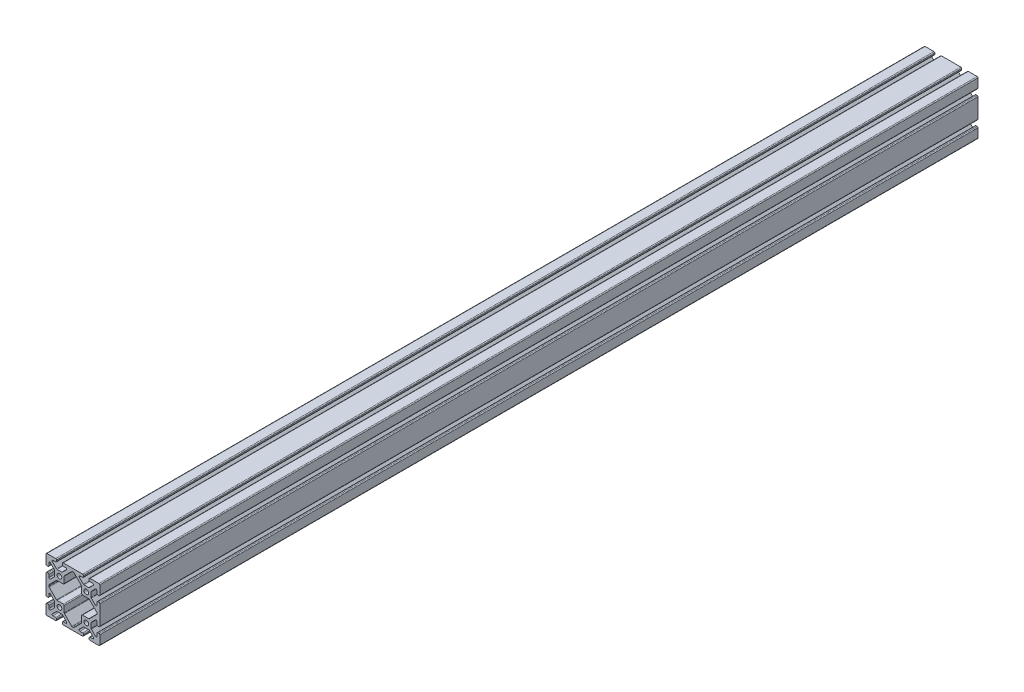
SolidWorks part; units mm, degrees
material "6061 Alloy"
ref_plane "Front Plane" through (0, 0, 0) normal (0, 0, 1) x (1, 0, 0)
ref_plane "Top Plane" through (0, 0, 0) normal (0, 1, 0) x (1, 0, 0)
ref_plane "Right Plane" through (0, 0, 0) normal (1, 0, 0) x (0, 0, -1)
sketch "Sketch1" plane through (0, 0, 0) normal (0, 0, 1) x (1, 0, 0)
  line L0 (-6.7564, 3.8827) -> (-6.7564, -6.7564)
  line L1 (-57.15, 19.05) -> (19.05, 19.05) construction
  line L2 (-6.7564, -6.7564) -> (3.8827, -6.7564)
  line L3 (-20.2403, -53.086) -> (-17.8597, -53.086)
  line L4 (19.05, 19.05) -> (19.05, -19.05) construction
  line L5 (-6.7564, -41.9827) -> (-17.8597, -53.086)
  line L6 (-20.2403, 14.986) -> (-17.8597, 14.986)
  line L7 (0, 0) -> (50000, 0) construction
  line L8 (-12.1123, 14.986) -> (-3.8827, 6.7564)
  line L9 (-34.036, 19.05) -> (-4.064, 19.05)
  line L10 (-4.064, 19.05) -> (-4.064, 14.986)
  line L11 (-4.064, 14.986) -> (-12.1123, 14.986)
  line L12 (-3.8827, 6.7564) -> (3.8827, 6.7564)
  line L13 (-6.7564, 3.8827) -> (-17.8597, 14.986)
  line L14 (-19.05, 19.05) -> (-19.05, 50019.05) construction
  line L15 (-57.15, 19.05) -> (-57.15, -19.05) construction
  line L16 (-53.086, -17.8597) -> (-53.086, -20.2403)
  line L17 (3.8827, -31.3436) -> (-6.7564, -31.3436)
  line L18 (19.05, 4.064) -> (14.986, 4.064)
  line L19 (19.05, 19.05) -> (19.05, 4.064)
  line L20 (14.986, 4.064) -> (14.986, 12.1123)
  line L21 (14.986, 12.1123) -> (6.7564, 3.8827)
  line L22 (6.7564, 3.8827) -> (6.7564, -3.8827)
  line L23 (12.1123, 14.986) -> (3.8827, 6.7564)
  line L24 (4.064, 14.986) -> (12.1123, 14.986)
  line L25 (4.064, 19.05) -> (4.064, 14.986)
  line L26 (19.05, 19.05) -> (4.064, 19.05)
  line L27 (14.986, -12.1123) -> (6.7564, -3.8827)
  line L28 (14.986, -4.064) -> (14.986, -12.1123)
  line L29 (19.05, -4.064) -> (14.986, -4.064)
  line L30 (19.05, -34.036) -> (19.05, -4.064)
  line L31 (-6.7564, -31.3436) -> (-6.7564, -41.9827)
  line L32 (-25.9877, -53.086) -> (-34.2173, -44.8564)
  line L33 (-34.036, -57.15) -> (-34.036, -53.086)
  line L34 (3.8827, -6.7564) -> (14.986, -17.8597)
  line L35 (-34.036, -53.086) -> (-25.9877, -53.086)
  line L36 (-34.2173, -44.8564) -> (-41.9827, -44.8564)
  line L37 (-57.15, -42.164) -> (-53.086, -42.164)
  line L38 (3.8827, -31.3436) -> (14.986, -20.2403)
  line L39 (-57.15, -57.15) -> (-57.15, -42.164)
  line L40 (-53.086, -42.164) -> (-53.086, -50.2123)
  line L41 (-53.086, -50.2123) -> (-44.8564, -41.9827)
  line L42 (-44.8564, -41.9827) -> (-44.8564, -34.2173)
  line L43 (-50.2123, -53.086) -> (-41.9827, -44.8564)
  line L44 (19.05, -34.036) -> (14.986, -34.036)
  line L45 (14.986, -34.036) -> (14.986, -25.9877)
  line L46 (14.986, -25.9877) -> (6.7564, -34.2173)
  line L47 (19.05, -57.15) -> (4.064, -57.15)
  line L48 (4.064, -57.15) -> (4.064, -53.086)
  line L49 (4.064, -53.086) -> (12.1123, -53.086)
  line L50 (12.1123, -53.086) -> (3.8827, -44.8564)
  line L51 (6.7564, -41.9827) -> (6.7564, -34.2173)
  line L52 (14.986, -50.2123) -> (6.7564, -41.9827)
  line L53 (14.986, -42.164) -> (14.986, -50.2123)
  line L54 (19.05, -57.15) -> (19.05, -42.164)
  line L55 (19.05, -42.164) -> (14.986, -42.164)
  line L56 (-42.164, -53.086) -> (-50.2123, -53.086)
  line L57 (-42.164, -57.15) -> (-42.164, -53.086)
  line L58 (-57.15, -57.15) -> (-42.164, -57.15)
  line L59 (-53.086, -25.9877) -> (-44.8564, -34.2173)
  line L60 (-53.086, -34.036) -> (-53.086, -25.9877)
  line L61 (-3.8827, -44.8564) -> (3.8827, -44.8564)
  line L62 (-4.064, -53.086) -> (-12.1123, -53.086)
  line L63 (-4.064, -57.15) -> (-4.064, -53.086)
  line L64 (-34.036, -57.15) -> (-4.064, -57.15)
  line L65 (-12.1123, -53.086) -> (-3.8827, -44.8564)
  line L66 (-57.15, -34.036) -> (-53.086, -34.036)
  line L67 (14.986, -17.8597) -> (14.986, -20.2403)
  line L68 (-41.9827, -31.3436) -> (-53.086, -20.2403)
  line L69 (-41.9827, -6.7564) -> (-53.086, -17.8597)
  line L70 (-31.3436, -31.3436) -> (-31.3436, -41.9827)
  line L71 (-57.15, -34.036) -> (-57.15, -4.064)
  line L72 (-57.15, -4.064) -> (-53.086, -4.064)
  line L73 (-53.086, -4.064) -> (-53.086, -12.1123)
  line L74 (-53.086, -12.1123) -> (-44.8564, -3.8827)
  line L75 (-57.15, 19.05) -> (-42.164, 19.05)
  line L76 (-42.164, 19.05) -> (-42.164, 14.986)
  line L77 (-42.164, 14.986) -> (-50.2123, 14.986)
  line L78 (-50.2123, 14.986) -> (-41.9827, 6.7564)
  line L79 (-44.8564, 3.8827) -> (-44.8564, -3.8827)
  line L80 (-53.086, 12.1123) -> (-44.8564, 3.8827)
  line L81 (-53.086, 4.064) -> (-53.086, 12.1123)
  line L82 (-57.15, 19.05) -> (-57.15, 4.064)
  line L83 (-57.15, 4.064) -> (-53.086, 4.064)
  line L84 (-41.9827, -31.3436) -> (-31.3436, -31.3436)
  line L85 (-31.3436, 3.8827) -> (-20.2403, 14.986)
  line L86 (-34.2173, 6.7564) -> (-41.9827, 6.7564)
  line L87 (-34.036, 14.986) -> (-25.9877, 14.986)
  line L88 (-34.036, 19.05) -> (-34.036, 14.986)
  line L89 (-25.9877, 14.986) -> (-34.2173, 6.7564)
  line L90 (-31.3436, -41.9827) -> (-20.2403, -53.086)
  line L91 (-31.3436, -6.7564) -> (-41.9827, -6.7564)
  line L92 (-31.3436, 3.8827) -> (-31.3436, -6.7564)
  circle A0 centre (0, 0) radius 3.3274
  circle A1 centre (0, -38.1) radius 3.3274
  circle A2 centre (-38.1, -38.1) radius 3.3274
  circle A3 centre (-38.1, 0) radius 3.3274
  point P0 (0, 0)
  point P2 (-19.05, 14.986)
  point P28 (0, 6.7564)
  point P32 (6.7564, 0)
  point P67 (-19.05, -57.15)
  point P75 (6.7564, -38.1)
  point P76 (0, -44.8564)
  point P110 (-19.05, 19.05)
  point P111 (-19.05, -53.086)
  point P112 (-38.1, -44.8564)
  point P113 (-44.8564, -38.1)
  point P114 (-44.8564, 0)
  point P115 (-38.1, 6.7564)
  dimension "D3" = 14.986
  dimension "D2" = 6.6548
  dimension "D4" = 4.064
  dimension "D6" = 12.2936
extrude "Boss-Extrude1" add sketch "Sketch1" along normal blind 1244.6
fillet "Fillet1" radius 1.27 87 edges at (-4.064, -53.086, 622.3) (-4.064, -57.15, 622.3) (3.8827, -44.8564, 622.3) (-3.8827, -44.8564, 622.3) (-12.1123, -53.086, 622.3) (4.064, -57.15, 622.3) (4.064, -53.086, 622.3) (12.1123, -53.086, 622.3) (19.05, -57.15, 622.3) (14.986, -42.164, 622.3) (19.05, -42.164, 622.3) (14.986, -50.2123, 622.3) (6.7564, -41.9827, 622.3) (6.7564, -34.2173, 622.3) (14.986, -25.9877, 622.3) (14.986, -34.036, 622.3) (19.05, -34.036, 622.3) (14.986, -12.1123, 622.3) (19.05, -4.064, 622.3) (14.986, -4.064, 622.3) (6.7564, -3.8827, 622.3) (6.7564, 3.8827, 622.3) (14.986, 4.064, 622.3) (19.05, 4.064, 622.3) (14.986, 12.1123, 622.3) (19.05, 19.05, 622.3) (4.064, 19.05, 622.3) (4.064, 14.986, 622.3) (12.1123, 14.986, 622.3) (3.8827, 6.7564, 622.3) (-3.8827, 6.7564, 622.3) (-12.1123, 14.986, 622.3) (-4.064, 14.986, 622.3) (-4.064, 19.05, 622.3) (14.986, -20.2403, 622.3) (14.986, -17.8597, 622.3) (-34.036, -57.15, 622.3) (-42.164, -57.15, 622.3) (-42.164, -53.086, 622.3) (-34.036, -53.086, 622.3) (-25.9877, -53.086, 622.3) (-34.2173, -44.8564, 622.3) (-41.9827, -44.8564, 622.3) (-50.2123, -53.086, 622.3) (-57.15, -57.15, 622.3) (-57.15, -34.036, 622.3) (-53.086, -34.036, 622.3) (-57.15, -42.164, 622.3) (-53.086, -42.164, 622.3) (-53.086, -50.2123, 622.3) (-44.8564, -41.9827, 622.3) (-44.8564, -34.2173, 622.3) (-53.086, -25.9877, 622.3) (3.8827, -31.3436, 622.3) (-6.7564, -31.3436, 622.3) (-17.8597, -53.086, 622.3) (-20.2403, -53.086, 622.3) (-31.3436, -41.9827, 622.3) (-31.3436, -31.3436, 622.3) (-41.9827, -31.3436, 622.3) (-53.086, -20.2403, 622.3) (-41.9827, 6.7564, 622.3) (-50.2123, 14.986, 622.3) (-42.164, 14.986, 622.3) (-42.164, 19.05, 622.3) (-57.15, 19.05, 622.3) (-57.15, 4.064, 622.3) (-53.086, 4.064, 622.3) (-53.086, 12.1123, 622.3) (-44.8564, 3.8827, 622.3) (-57.15, -4.064, 622.3) (-44.8564, -3.8827, 622.3) (-53.086, -4.064, 622.3) (-53.086, -12.1123, 622.3) (-53.086, -17.8597, 622.3) (-41.9827, -6.7564, 622.3) (-31.3436, -6.7564, 622.3) (-31.3436, 3.8827, 622.3) (-34.2173, 6.7564, 622.3) (-34.036, 14.986, 622.3) (-34.036, 19.05, 622.3) (-25.9877, 14.986, 622.3) (-20.2403, 14.986, 622.3) (-17.8597, 14.986, 622.3) (-6.7564, -6.7564, 622.3) (3.8827, -6.7564, 622.3) (-6.7564, 3.8827, 622.3)
